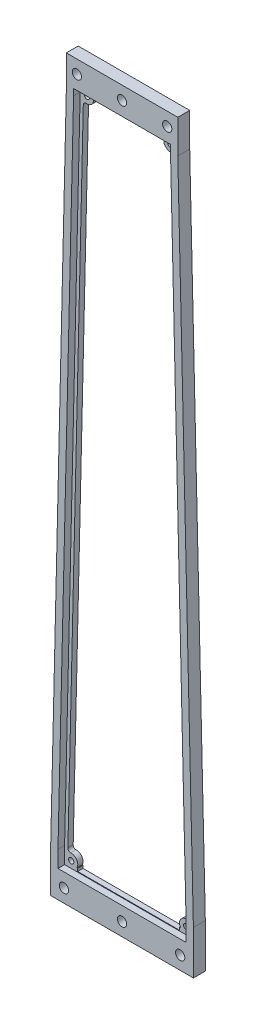
SolidWorks part; units mm, degrees
ref_plane "前视基准面" through (0, 0, 0) normal (0, 0, 1) x (1, 0, 0)
ref_plane "上视基准面" through (0, 0, 0) normal (0, 1, 0) x (1, 0, 0)
ref_plane "右视基准面" through (0, 0, 0) normal (1, 0, 0) x (0, 0, -1)
other "Configuration Table"
sketch "草图2" plane through (0, 0, -1.5384) normal (0, 0, -1) x (-1, 0, 0)
  line L2 (-17.1349, 121.1324) -> (-22.943, -124.6622)
  line L3 (-22.943, -124.6622) -> (-22.943, -124.7776)
  line L4 (-19.646, -129.6706) -> (-19.235, -129.6706)
  line L6 (22.943, -124.6622) -> (17.1349, 121.1324)
  line L8 (18.0521, 126.8606) -> (-18.0521, 126.8606)
  line L9 (-18.0521, 126.8606) -> (-18.0521, 124.6502)
  line L10 (-18.0521, 124.6502) -> (-23.943, -124.6504)
  line L11 (-23.943, -124.6504) -> (-23.943, -130.6706)
  line L12 (-23.943, -130.6706) -> (23.943, -130.6706)
  line L13 (23.943, -130.6706) -> (23.943, -124.6504)
  line L14 (23.943, -124.6504) -> (18.0521, 124.6499)
  line L15 (18.0521, 124.6499) -> (18.0521, 126.8606)
  line L16 (18.0521, 126.8606) -> (-18.0521, 126.8606)
  line L17 (-18.0521, 126.8606) -> (-18.0521, 124.6502)
  line L18 (-18.0521, 124.6502) -> (-23.943, -124.6504)
  line L19 (-23.943, -124.6504) -> (-23.943, -130.6706)
  line L20 (-23.943, -130.6706) -> (23.943, -130.6706)
  line L21 (23.943, -130.6706) -> (23.943, -124.6504)
  line L22 (23.943, -124.6504) -> (18.0521, 124.6499)
  line L23 (18.0521, 124.6499) -> (18.0521, 126.8606)
  line L24 (22.943, -124.9046) -> (22.943, -124.6622)
  line L25 (17.0521, 125.8606) -> (-17.0521, 125.8606) construction
  line L26 (-17.0521, 125.8606) -> (-17.0521, 124.6384) construction
  line L27 (-17.0521, 124.6384) -> (-22.943, -124.6622) construction
  line L28 (22.943, -124.6622) -> (17.0521, 124.6381) construction
  line L29 (17.0521, 124.6381) -> (17.0521, 125.8606) construction
  line L30 (12.2587, 125.8606) -> (-12.2587, 125.8606)
  line L31 (-22.943, -124.6622) -> (-22.943, -129.6706) construction
  line L32 (-22.943, -129.6706) -> (22.943, -129.6706) construction
  line L33 (22.943, -129.6706) -> (22.943, -124.6622) construction
  line L34 (-19.235, -130.6706) -> (-19.235, -129.6706)
  line L35 (-18.735, -130.4792) -> (-18.735, -126.2792) construction
  line L36 (19.265, -129.6706) -> (19.5656, -129.6706)
  line L37 (19.265, -129.6706) -> (19.265, -130.6706)
  line L38 (18.765, -125.8792) -> (18.765, -125.3792) construction
  circle A0 centre (21.717, -128.3973) radius 1 construction
  circle A1 centre (-21.717, -128.2703) radius 1 construction
  circle A2 centre (-15.748, 124.5872) radius 1 construction
  circle A3 centre (15.748, 124.5872) radius 1 construction
  circle A4 centre (21.717, -128.3973) radius 1 construction
  circle A5 centre (-21.717, -128.2703) radius 1 construction
  circle A6 centre (-15.748, 124.5872) radius 1 construction
  circle A7 centre (15.748, 124.5872) radius 1 construction
  circle A8 centre (-15.748, 124.5872) radius 1
  circle A9 centre (15.748, 124.5872) radius 1
  circle A10 centre (-21.717, -128.2703) radius 1
  circle A11 centre (21.717, -128.3973) radius 1
  arc A12 (-16.0246, 122.1026) -> (-13.2557, 124.7825) centre (-15.748, 124.5872) ccw
  arc A13 (-19.646, -129.6706) -> (-21.8784, -125.7755) centre (-21.717, -128.2703) ccw
  arc A14 (13.2557, 124.7825) -> (16.0246, 122.1026) centre (15.748, 124.5872) ccw
  arc A15 (21.8784, -125.9025) -> (19.5656, -129.6706) centre (21.717, -128.3973) ccw
  arc A16 (17.1349, 121.1324) -> (16.0246, 122.1026) centre (16.1352, 121.1087) ccw
  arc A17 (13.2557, 124.7825) -> (12.2587, 125.8606) centre (12.2587, 124.8606) ccw
  arc A18 (-13.2557, 124.7825) -> (-12.2587, 125.8606) centre (-12.2587, 124.8606) cw
  arc A19 (-17.1349, 121.1324) -> (-16.0246, 122.1026) centre (-16.1352, 121.1087) cw
  arc A20 (21.8784, -125.9025) -> (22.943, -124.9046) centre (21.943, -124.9046) ccw
  arc A21 (-21.8784, -125.7755) -> (-22.943, -124.7776) centre (-21.943, -124.7776) cw
  line M48 (18.0521, 126.8606) -> (-18.0521, 126.8606)
  line M49 (-18.0521, 126.8606) -> (-18.0521, 124.6502)
  line M50 (-18.0521, 124.6502) -> (-23.943, -124.6504)
  line M51 (-23.943, -124.6504) -> (-23.943, -130.6706)
  line M52 (-23.943, -130.6706) -> (23.943, -130.6706)
  line M53 (23.943, -130.6706) -> (23.943, -124.6504)
  line M54 (23.943, -124.6504) -> (18.0521, 124.6499)
  line M55 (18.0521, 124.6499) -> (18.0521, 126.8606)
  dimension "D3" = 2
  dimension "D4" = 2
  dimension "D5" = 2
  dimension "D6" = 2
  dimension "D7" = 2
  dimension "D8" = 5
  dimension "D9" = 5
  dimension "D10" = 5
  dimension "D12" = 5
  dimension "D13" = 1
  dimension "D11" = 1
  dimension "D15" = 0.5
  dimension "D16" = 0.5
  dimension "D17" = 1
  dimension "D1" = 0
  dimension "D2" = 1
extrude "凸台-拉伸1" add sketch "草图2" along normal blind 2 contours A13 A21 L3 L2 A19 A12 A18 L30 A17 A14 A16 L6 L24 A20 A15 L36 L37 L34 L4 A8 A9 A10 A11 M52 M53 M54 M55 M48 M49 M50 M51
sketch "草图3" plane through (0, 0, -3.5384) normal (0, 0, -1) x (-1, 0, 0)
  line L0 (26.943, -124.615) -> (21.0521, 124.6854)
  line L1 (21.0521, 124.6854) -> (21.0521, 129.8606)
  line L2 (21.0521, 129.8606) -> (-21.0521, 129.8606)
  line L3 (-21.0521, 129.8606) -> (-21.0521, 124.6857)
  line L4 (-21.0521, 124.6857) -> (-26.943, -124.615)
  line L5 (-26.943, -124.615) -> (-26.943, -133.6706)
  line L6 (-26.943, -133.6706) -> (26.943, -133.6706)
  line L7 (26.943, -133.6706) -> (26.943, -124.615)
  line L8 (18.0521, 126.8606) -> (-18.0521, 126.8606)
  line L9 (-18.0521, 126.8606) -> (-18.0521, 124.6502)
  line L10 (-18.0521, 124.6502) -> (-23.943, -124.6504)
  line L11 (-23.943, -124.6504) -> (-23.943, -130.6706)
  line L12 (-23.943, -130.6706) -> (23.943, -130.6706)
  line L13 (23.943, -130.6706) -> (23.943, -124.6504)
  line L14 (23.943, -124.6504) -> (18.0521, 124.6499)
  line L15 (18.0521, 124.6499) -> (18.0521, 126.8606)
  line L16 (18.0521, 126.8606) -> (-18.0521, 126.8606)
  line L17 (-18.0521, 126.8606) -> (-18.0521, 124.6502)
  line L18 (-18.0521, 124.6502) -> (-23.943, -124.6504)
  line L19 (-23.943, -124.6504) -> (-23.943, -130.6706)
  line L20 (-23.943, -130.6706) -> (23.943, -130.6706)
  line L21 (23.943, -130.6706) -> (23.943, -124.6504)
  line L22 (23.943, -124.6504) -> (18.0521, 124.6499)
  line L23 (18.0521, 124.6499) -> (18.0521, 126.8606)
  dimension "D1" = 0
  dimension "D2" = 3
extrude "凸台-拉伸2" add sketch "草图3" against normal blind 2
sketch "草图4" plane through (0, 0, -1.5384) normal (0, 0, 1) x (1, 0, 0)
  line L0 (-18.3021, 124.6529) -> (-24.193, -124.6474)
  line L1 (-24.193, -124.6474) -> (-24.193, -130.9206)
  line L2 (-24.193, -130.9206) -> (24.193, -130.9206)
  line L3 (24.193, -130.9206) -> (24.193, -124.6474)
  line L4 (24.193, -124.6474) -> (18.3021, 124.6532)
  line L5 (18.3021, 124.6532) -> (18.3021, 127.1106)
  line L6 (18.3021, 127.1106) -> (-18.3021, 127.1106)
  line L7 (-18.3021, 127.1106) -> (-18.3021, 124.6529)
  line L8 (-26.943, -124.615) -> (-26.943, -133.6706)
  line L9 (-26.943, -133.6706) -> (26.943, -133.6706)
  line L10 (26.943, -133.6706) -> (26.943, -124.615)
  line L11 (26.943, -124.615) -> (21.0521, 124.6857)
  line L12 (21.0521, 124.6857) -> (21.0521, 129.8606)
  line L13 (21.0521, 129.8606) -> (-21.0521, 129.8606)
  line L14 (-21.0521, 129.8606) -> (-21.0521, 124.6854)
  line L15 (-21.0521, 124.6854) -> (-26.943, -124.615)
  line L16 (-26.943, -124.615) -> (-26.943, -133.6706)
  line L17 (-26.943, -133.6706) -> (26.943, -133.6706)
  line L18 (26.943, -133.6706) -> (26.943, -124.615)
  line L19 (26.943, -124.615) -> (21.0521, 124.6857)
  line L20 (21.0521, 124.6857) -> (21.0521, 129.8606)
  line L21 (21.0521, 129.8606) -> (-21.0521, 129.8606)
  line L22 (-21.0521, 129.8606) -> (-21.0521, 124.6854)
  line L23 (-21.0521, 124.6854) -> (-26.943, -124.615)
  line L24 (-18.0521, 126.8606) -> (-18.0521, 124.6499)
  line L25 (-18.0521, 124.6499) -> (-23.943, -124.6504)
  line L26 (-23.943, -124.6504) -> (-23.943, -130.6706)
  line L27 (-23.943, -130.6706) -> (23.943, -130.6706)
  line L28 (23.943, -130.6706) -> (23.943, -124.6504)
  line L29 (23.943, -124.6504) -> (18.0521, 124.6502)
  line L30 (18.0521, 124.6502) -> (18.0521, 126.8606)
  line L31 (18.0521, 126.8606) -> (-18.0521, 126.8606)
  line L32 (-18.0521, 126.8606) -> (-18.0521, 124.6499)
  line L33 (-18.0521, 124.6499) -> (-23.943, -124.6504)
  line L34 (-23.943, -124.6504) -> (-23.943, -130.6706)
  line L35 (-23.943, -130.6706) -> (23.943, -130.6706)
  line L36 (23.943, -130.6706) -> (23.943, -124.6504)
  line L37 (23.943, -124.6504) -> (18.0521, 124.6502)
  line L38 (18.0521, 124.6502) -> (18.0521, 126.8606)
  line L39 (18.0521, 126.8606) -> (-18.0521, 126.8606)
  line M41 (-26.943, -124.615) -> (-26.943, -133.6706)
  line M42 (-26.943, -133.6706) -> (26.943, -133.6706)
  line M43 (26.943, -133.6706) -> (26.943, -124.615)
  line M44 (26.943, -124.615) -> (21.0521, 124.6857)
  line M45 (21.0521, 124.6857) -> (21.0521, 129.8606)
  line M46 (21.0521, 129.8606) -> (-21.0521, 129.8606)
  line M47 (-21.0521, 129.8606) -> (-21.0521, 124.6854)
  line M48 (-21.0521, 124.6854) -> (-26.943, -124.615)
  dimension "D1" = 0
  dimension "D2" = 0
  dimension "D3" = 0.25
extrude "凸台-拉伸3" add sketch "草图4" along normal blind 2.5 contours L7 L6 L5 L4 L3 L2 L1 L0 M48 M41 M42 M43 M44 M45 M46 M47
sketch "草图5" plane through (0, 0, 0.9616) normal (0, 0, 1) x (1, 0, 0)
  line L0 (-26.943, -133.6706) -> (26.943, -133.6706) construction
  line L1 (21.0521, 129.8606) -> (-21.0521, 129.8606) construction
  line L2 (-26.943, -133.6706) -> (26.943, -133.6706)
  line L3 (21.0521, 129.8606) -> (-21.0521, 129.8606)
  line L4 (-1021.0521, 132.3606) -> (48978.9479, 132.3606) construction
  line L5 (-21.0521, 129.8606) -> (21.0521, 129.8606)
  line L6 (-21.0521, 129.8606) -> (-21.0521, 134.8606)
  line L7 (-21.0521, 134.8606) -> (21.0521, 134.8606) construction
  line L8 (21.0521, 129.8606) -> (21.0521, 134.8606)
  line L9 (-26.943, -133.6706) -> (26.943, -133.6706)
  line L10 (-26.943, -133.6706) -> (-26.943, -138.6706)
  line L11 (-26.943, -138.6706) -> (26.943, -138.6706) construction
  line L12 (26.943, -133.6706) -> (26.943, -138.6706)
  line L13 (0, -865.1394) -> (0, 49134.8606) construction
  line L14 (-1026.943, -136.1706) -> (48973.057, -136.1706) construction
  line L16 (-21.0521, 134.8606) -> (21.0521, 134.8606) construction
  line L17 (-21.0521, 134.8606) -> (-21.0521, 137.3606)
  line L18 (-21.0521, 137.3606) -> (21.0521, 137.3606)
  line L19 (21.0521, 134.8606) -> (21.0521, 137.3606)
  line L20 (-26.943, -138.6706) -> (26.943, -138.6706) construction
  line L21 (-26.943, -138.6706) -> (-26.943, -141.1706)
  line L22 (-26.943, -141.1706) -> (26.943, -141.1706)
  line L23 (26.943, -138.6706) -> (26.943, -141.1706)
  circle A0 centre (-17.0521, 132.3606) radius 1.75
  circle A1 centre (17.0521, 132.3606) radius 1.75
  circle A2 centre (0, 132.3606) radius 1.75
  circle A3 centre (0, -136.1706) radius 1.75
  circle A4 centre (21.943, -136.1706) radius 1.75
  circle A5 centre (-21.943, -136.1706) radius 1.75
  point P11 (-21.0521, 132.3606)
  point P20 (0, 134.8606)
  point P25 (-26.943, -136.1706)
  line M17 (-26.943, -133.6706) -> (26.943, -133.6706)
  line M21 (21.0521, 129.8606) -> (-21.0521, 129.8606)
  dimension "D3" = 3.5
  dimension "D5" = 3.5
  dimension "D7" = 3.5
  dimension "D8" = 3.5
  dimension "D9" = 3.5
  dimension "D11" = 3.5
  dimension "D1" = 5
  dimension "D2" = 5
  dimension "D4" = 4
  dimension "D6" = 4
  dimension "D10" = 5
  dimension "D12" = 5
  dimension "D13" = 2.5
  dimension "D14" = 2.5
extrude "凸台-拉伸4" add sketch "草图5" against normal up to surface (4.5 mm away) contours L8 L7 L6 A2 A1 A0 M21 | L12 L10 L11 A5 A4 A3 M17
